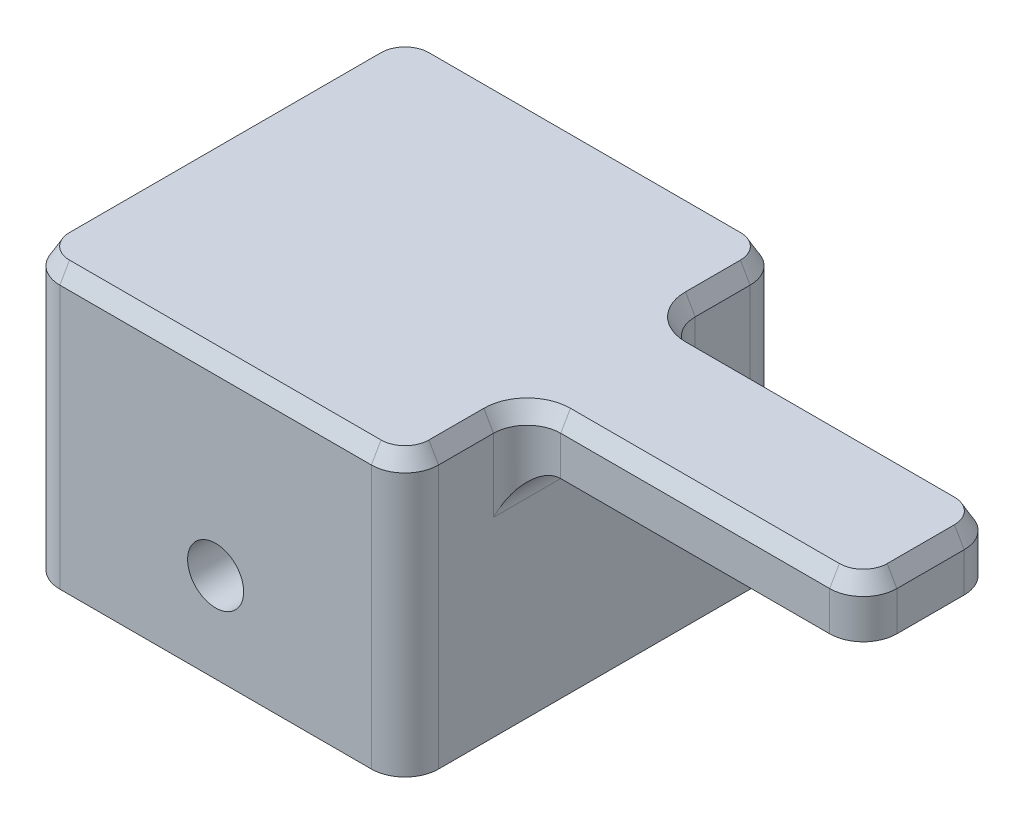
SolidWorks part; units mm, degrees
ref_plane "Front Plane" through (0, 0, 0) normal (0, 0, 1) x (1, 0, 0)
ref_plane "Top Plane" through (0, 0, 0) normal (0, 1, 0) x (1, 0, 0)
ref_plane "Right Plane" through (0, 0, 0) normal (1, 0, 0) x (0, 0, -1)
sketch "Sketch1" plane through (0, 0, 0) normal (0, 1, 0) x (1, 0, 0)
  line L0 (-16.9, -16.9) -> (-16.9, 16.9)
  line L1 (-12.9, -12.9) -> (12.9, -12.9)
  line L2 (-12.9, -12.9) -> (-12.9, 12.9)
  line L3 (-12.9, 12.9) -> (12.9, 12.9)
  line L4 (12.9, -12.9) -> (12.9, 12.9)
  line L5 (-12.9, -12.9) -> (12.9, 12.9) construction
  line L6 (-12.9, 12.9) -> (12.9, -12.9) construction
  line L7 (-16.9, 16.9) -> (16.9, 16.9)
  line L8 (16.9, -16.9) -> (16.9, 16.9)
  line L9 (-16.9, -16.9) -> (16.9, -16.9)
  point P0 (0, 0)
  dimension "D2" = 25.8
  dimension "D1" = 4
extrude "Boss-Extrude1" add sketch "Sketch1" along normal blind 20
sketch "Sketch2" plane through (0, 20, 0) normal (0, 1, 0) x (1, 0, 0)
  line L0 (-16.9, -16.9) -> (16.9, -16.9) construction
  line L1 (-16.9, 16.9) -> (16.9, 16.9)
  line L2 (-16.9, 16.9) -> (-16.9, -16.9)
  line L3 (-16.9, -16.9) -> (16.9, -16.9)
  line L4 (16.9, 16.9) -> (16.9, -16.9)
  line L5 (16.9, -16.9) -> (16.9, 16.9) construction
  line L6 (16.9, 6) -> (46.9, 6)
  line L7 (46.9, 6) -> (46.9, -6)
  line L8 (46.9, -6) -> (16.9, -6)
  point P12 (46.9, 0)
  point P15 (16.9, 0)
  line M9 (-16.9, -16.9) -> (16.9, -16.9)
  line M10 (16.9, -16.9) -> (16.9, 16.9)
  line M11 (16.9, 16.9) -> (-16.9, 16.9)
  line M12 (-16.9, 16.9) -> (-16.9, -16.9)
  line M13 (-12.9, 12.9) -> (12.9, 12.9)
  line M14 (12.9, 12.9) -> (12.9, -12.9)
  line M15 (12.9, -12.9) -> (-12.9, -12.9)
  line M16 (-12.9, -12.9) -> (-12.9, 12.9)
  dimension "D1" = 30
  dimension "D2" = 12
extrude "Boss-Extrude2" add sketch "Sketch2" along normal blind 5 contours L8 L7 L6 L4 | M13 M16 M15 M14 | L4 M12 M9 M10 M11 M16 M13 M14 M15
sketch "Sketch3" plane through (0, 0, 16.9) normal (0, 0, 1) x (1, 0, 0)
  line L0 (-16.9, 0) -> (16.9, 0) construction
  circle A0 centre (0, 8) radius 2.5
  point P2 (0, 0)
  dimension "D1" = 5
  dimension "D2" = 8
extrude "Cut-Extrude1" cut sketch "Sketch3" against normal up to next
fillet "Fillet1" radius 3 9 edges at (16.9, 12.5, 16.9) (-16.9, 12.5, 16.9) (-16.9, 12.5, -16.9) (16.9, 12.5, -16.9) (16.9, 22.5, -6) (16.9, 22.5, 6) (16.9, 20, 0) (46.9, 22.5, -6) (46.9, 22.5, 6)
chamfer "Chamfer1" distance 1.5 angle 30 16 edges at (-16.0213, 25, 16.0213) (-16.9, 25, 0) (-16.0213, 25, -16.0213) (0, 25, -16.9) (16.0213, 25, -16.0213) (16.9, 25, -11.45) (17.7787, 25, -6.8787) (31.9, 25, -6) (46.0213, 25, -5.1213) (46.9, 25, 0) (46.0213, 25, 5.1213) (31.9, 25, 6) (17.7787, 25, 6.8787) (16.9, 25, 11.45) (16.0213, 25, 16.0213) (0, 25, 16.9)
